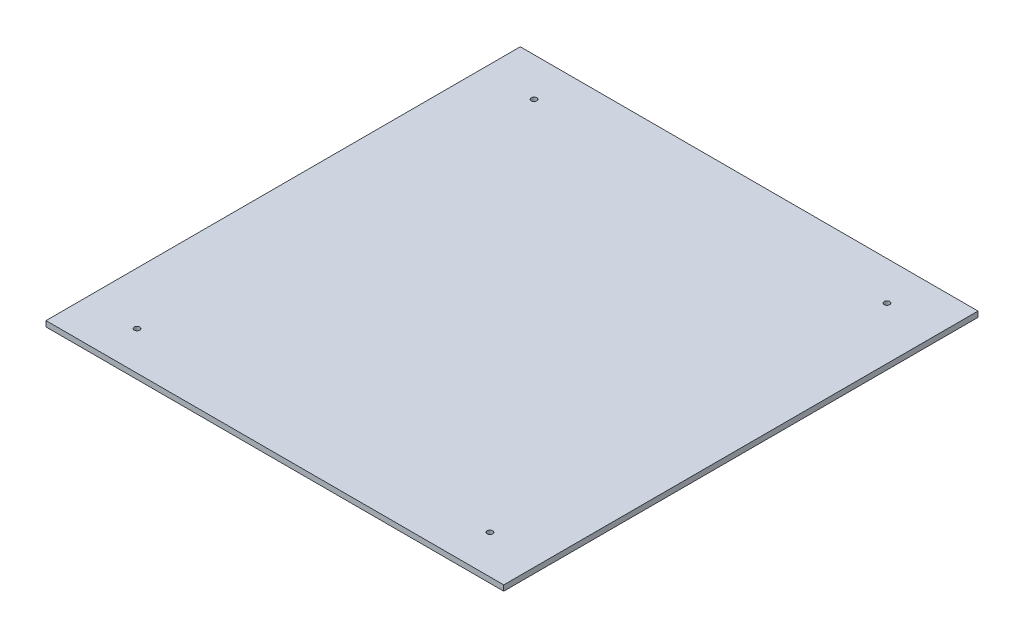
SolidWorks part; units mm, degrees
ref_plane "Alzado" through (0, 0, 0) normal (0, 0, 1) x (1, 0, 0)
ref_plane "Planta" through (0, 0, 0) normal (0, 1, 0) x (1, 0, 0)
ref_plane "Vista lateral" through (0, 0, 0) normal (1, 0, 0) x (0, 0, -1)
sketch "Croquis1" plane through (0, 0, 0) normal (0, 1, 0) x (1, 0, 0)
  line L1 (207.5, -215) -> (-207.5, -215)
  line L2 (207.5, -215) -> (207.5, 215)
  line L3 (207.5, 215) -> (-207.5, 215)
  line L4 (-207.5, -215) -> (-207.5, 215)
  line L5 (207.5, -215) -> (-207.5, 215) construction
  line L6 (207.5, 215) -> (-207.5, -215) construction
  point P0 (0, 0)
  dimension "D1" = 430
  dimension "D2" = 415
extrude "Saliente-Extruir1" add sketch "Croquis1" along normal blind 5
sketch "Croquis2" plane through (0, 5, 0) normal (0, 1, 0) x (1, 0, 0)
  line L0 (0, 256.8961) -> (0, -255.1691) construction
  line L1 (242.6481, 0) -> (-300.5037, 0) construction
  line L2 (207.5, 215) -> (-207.5, 215) construction
  circle A0 centre (-160, 180) radius 2.5
  circle A1 centre (160, 180) radius 2.5
  circle A2 centre (160, -180) radius 2.5
  circle A3 centre (-160, -180) radius 2.5
  dimension "D1" = 160
  dimension "D4" = 5
  dimension "D2" = 215
  dimension "D3" = 180
extrude "Cortar-Extruir1" cut sketch "Croquis2" against normal through all
